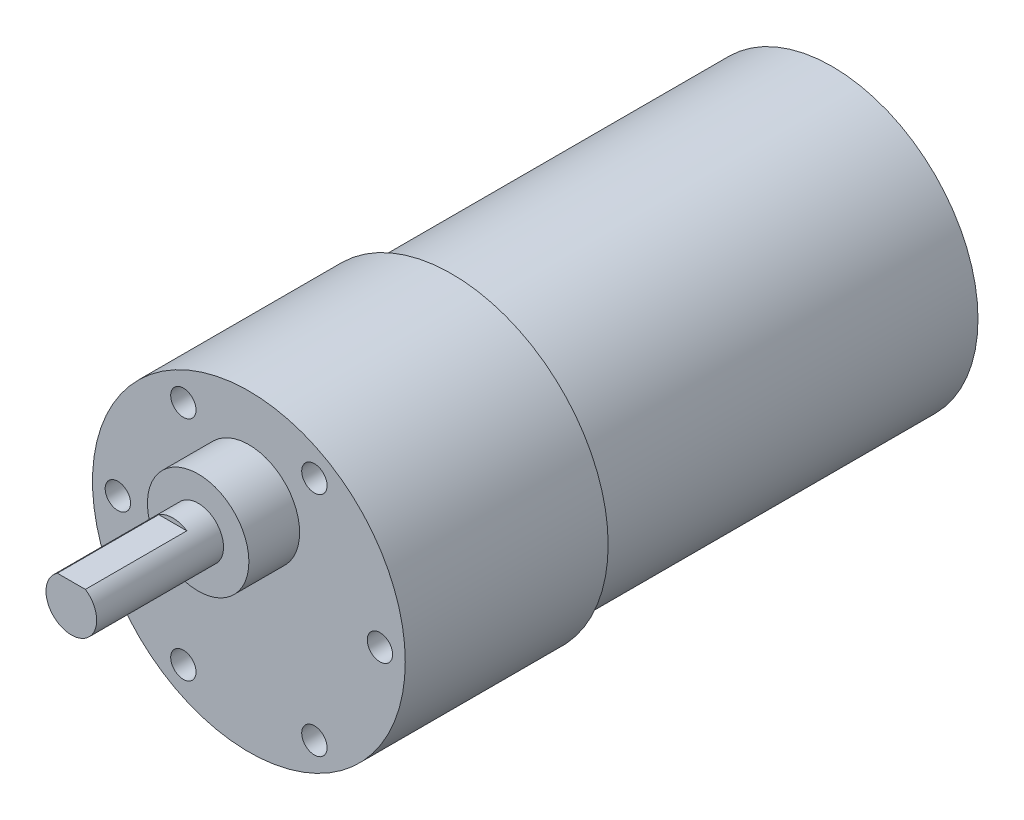
SolidWorks part; units mm, degrees
ref_plane "Front Plane" through (0, 0, 0) normal (0, 0, 1) x (1, 0, 0)
ref_plane "Top Plane" through (0, 0, 0) normal (0, 1, 0) x (1, 0, 0)
ref_plane "Right Plane" through (0, 0, 0) normal (1, 0, 0) x (0, 0, -1)
sketch "Sketch1" plane through (0, 0, 0) normal (0, 0, 1) x (1, 0, 0)
  circle A0 centre (0, 0) radius 18.5
  dimension "D1" = 37
extrude "Boss-Extrude1" add sketch "Sketch1" along normal blind 24
sketch "Sketch2" plane through (0, 0, 0) normal (0, 0, -1) x (-1, 0, 0)
  circle A0 centre (0, 0) radius 17.25
  dimension "D1" = 34.5
extrude "Boss-Extrude2" add sketch "Sketch2" along normal blind 45
sketch "Sketch3" plane through (0, 0, 24) normal (0, 0, 1) x (1, 0, 0)
  line L0 (0, 0) -> (0, 18.5) construction
  circle A0 centre (0, 0) radius 18.5 construction
  circle A1 centre (0, 7) radius 6
  dimension "D2" = 12
  dimension "D1" = 7
extrude "Boss-Extrude3" add sketch "Sketch3" along normal blind 6
sketch "Sketch4" plane through (0, 0, 30) normal (0, 0, 1) x (1, 0, 0)
  circle A0 centre (0, 7) radius 3
  circle A1 centre (0, 7) radius 6 construction
  dimension "D1" = 6
extrude "Boss-Extrude4" add sketch "Sketch4" along normal blind 15
sketch "Sketch5" plane through (0, 0, 45) normal (0, 0, 1) x (1, 0, 0)
  line L0 (-1.6583, 9.5) -> (1.6583, 9.5)
  line L1 (0, 9.5) -> (0, 4)
  circle A0 centre (0, 7) radius 3
  circle A1 centre (0, 7) radius 3 construction
  circle M1 centre (0, 7) radius 3
  dimension "D1" = 5.5
extrude "Cut-Extrude1" cut sketch "Sketch5" against normal blind 12 contours L0 M1
sketch "Sketch6" plane through (0, 0, 24) normal (0, 0, 1) x (1, 0, 0)
  line L0 (0, 18.5) -> (0, 0) construction
  line L1 (0, 0) -> (9.25, 16.0215) construction
  circle A0 centre (7.75, 13.4234) radius 1.5
  circle A3 centre (0, 0) radius 18.5 construction
  circle A4 centre (0, 0) radius 15.5 construction
  circle A5 centre (15.5, 0) radius 1.5
  circle A6 centre (7.75, -13.4234) radius 1.5
  circle A7 centre (-7.75, -13.4234) radius 1.5
  circle A8 centre (-15.5, 0) radius 1.5
  circle A9 centre (-7.75, 13.4234) radius 1.5
  point P21 (0, 0)
  dimension "D2" = 31
  dimension "D4" = 3
  dimension "D1" = 30
  dimension "D3" = 6
extrude "Cut-Extrude2" cut sketch "Sketch6" against normal blind 3
